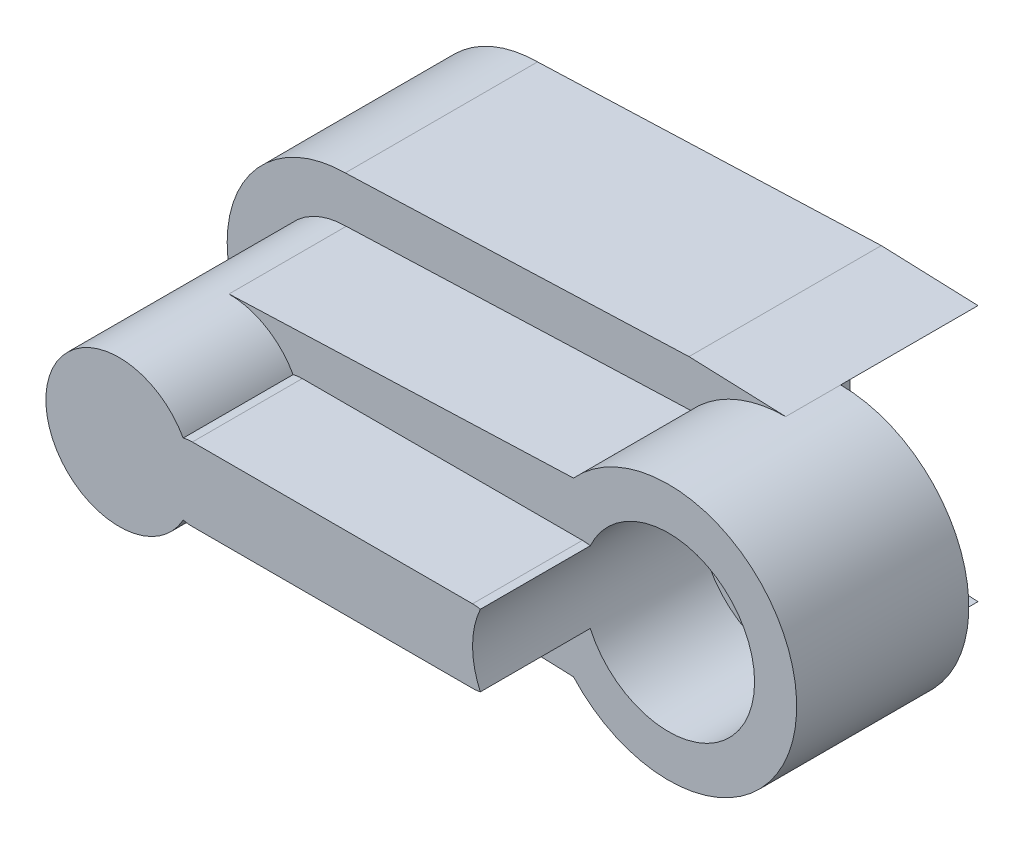
SolidWorks part; units mm, degrees
ref_plane "Front Plane" through (0, 0, 0) normal (0, 0, 1) x (1, 0, 0)
ref_plane "Top Plane" through (0, 0, 0) normal (0, 1, 0) x (1, 0, 0)
ref_plane "Right Plane" through (0, 0, 0) normal (1, 0, 0) x (0, 0, -1)
sketch "Sketch1" plane through (0, 0, 0) normal (0, 0, 1) x (1, 0, 0)
  line L4 (-10.9395, 2) -> (-1.5333, 2.35)
  line L5 (-10.9395, -2) -> (-1.5333, -2.35)
  circle A1 centre (1.0605, 0) radius 3.5
  circle A2 centre (-10.9395, 0) radius 2
  circle A3 centre (1.0605, 0) radius 2.35
  dimension "D2" = 7
  dimension "D6" = 4
  dimension "D1" = 4.7
  dimension "D5" = 4.7
  dimension "D7" = 12
  dimension "D8" = 9.4063
extrude "Boss-Extrude1" add sketch "Sketch1" along normal blind 6.7 contours A2 L5 A1 L4 | A1 | A2
sketch "Sketch2" plane through (0, 0, 6.7) normal (0, 0, 1) x (1, 0, 0)
  line L0 (-8.9395, 0) -> (-1.2895, 0) construction
  line L1 (-8.9395, 0) -> (-1.2895, 0) construction
  line L2 (-8.9395, 1) -> (-1.2895, 1)
  line L3 (-8.9395, -1) -> (-1.2895, -1)
  arc A1 (-9.1895, 0.9682) -> (-9.1895, -0.9682) centre (-10.9395, 0) ccw
  circle A2 centre (1.0605, 0) radius 2.35 construction
  arc A3 (-8.9395, 1) -> (-9.1895, 0.9682) centre (-8.9395, 0) ccw
  arc A4 (-1.2895, -1) -> (-1.0768, -0.9771) centre (-1.2895, 0) ccw
  arc A5 (-1.0768, 0.9771) -> (-1.0768, -0.9771) centre (1.0605, 0) ccw
  arc A6 (-1.0768, 0.9771) -> (-1.2895, 1) centre (-1.2895, 0) ccw
  arc A7 (-9.1895, -0.9682) -> (-8.9395, -1) centre (-8.9395, 0) ccw
  point P8 (-5.1145, 0)
extrude "Boss-Extrude2" add sketch "Sketch2" along normal blind 3
sketch "Sketch3" plane through (0, 0, 0) normal (0, 0, -1) x (-1, 0, 0)
  line L2 (10.9395, 2) -> (1.5333, 2.35)
  line L3 (1.5333, -2.35) -> (10.9395, -2)
  line L4 (10.9395, 2) -> (1.5333, 2.35)
  line L5 (1.5333, -2.35) -> (10.9395, -2)
  arc A2 (1.5333, 2.35) -> (1.5333, -2.35) centre (-1.0605, 0) ccw
  arc A3 (10.9395, -2) -> (10.9395, 2) centre (10.9395, 0) ccw
  arc A4 (1.5333, 2.35) -> (1.5333, -2.35) centre (-1.0605, 0) ccw
  arc A5 (10.9395, -2) -> (10.9395, 2) centre (10.9395, 0) ccw
  dimension "D1" = 0
extrude "Cut-Extrude1" cut sketch "Sketch3" against normal blind 2
sketch "Sketch4" plane through (0, 0, 2) normal (0, 0, -1) x (-1, 0, 0)
  circle A0 centre (-1.0605, 0) radius 1.45
  circle A1 centre (-1.0605, 0) radius 2.35
  dimension "D1" = 2.9
extrude "Boss-Extrude3" add sketch "Sketch4" against normal blind 1.5
sketch "Sketch5" plane through (0, 0, 2) normal (0, 0, -1) x (-1, 0, 0)
  line L0 (1.5797, -3.5991) -> (10.986, -3.2491)
  line L1 (10.986, 3.2491) -> (1.5797, 3.5991)
  line L3 (10.9656, 3.2499) -> (2.0599, 3.5813)
  line L7 (2.0599, -3.5813) -> (10.9656, -3.2499)
  line L8 (10.9395, 2) -> (1.5333, 2.35)
  line L9 (1.5333, -2.35) -> (10.9395, -2)
  line L10 (10.9395, 2) -> (1.5333, 2.35)
  line L11 (1.5333, -2.35) -> (10.9395, -2)
  line L13 (1.5797, -3.5991) -> (-1.0605, -3.5)
  line L14 (8.9395, -1) -> (1.2895, -1)
  line L15 (1.5333, -2.35) -> (10.9395, -2)
  line L16 (10.9395, 2) -> (1.5333, 2.35)
  line L17 (1.2895, 1) -> (8.9395, 1)
  line L19 (1.5333, -2.35) -> (10.9395, -2)
  line L20 (10.9395, 2) -> (1.5333, 2.35)
  line L22 (1.5797, 3.5991) -> (-1.0605, 3.5)
  arc A0 (10.9656, -3.2499) -> (10.9656, 3.2499) centre (10.9395, 0) ccw
  arc A6 (10.9395, -2) -> (10.9395, 2) centre (10.9395, 0) ccw
  arc A7 (1.5333, 2.35) -> (1.5333, -2.35) centre (-1.0605, 0) ccw
  arc A8 (10.9395, -2) -> (10.9395, 2) centre (10.9395, 0) ccw
  arc A10 (1.5333, 2.35) -> (1.5333, -2.35) centre (-1.0605, 0) ccw construction
  arc A11 (1.5333, 2.35) -> (-1.0605, 3.5) centre (-1.0605, 0) ccw
  arc A12 (1.2895, 1) -> (1.0768, 0.9771) centre (1.2895, 0) ccw
  arc A13 (1.0768, 0.9771) -> (1.0768, -0.9771) centre (-1.0605, 0) ccw
  arc A14 (1.0768, -0.9771) -> (1.2895, -1) centre (1.2895, 0) ccw
  arc A15 (8.9395, -1) -> (9.1895, -0.9682) centre (8.9395, 0) ccw
  arc A16 (9.1895, -0.9682) -> (10.9395, -2) centre (10.9395, 0) ccw
  arc A17 (1.5333, 2.35) -> (1.5333, -2.35) centre (-1.0605, 0) ccw
  arc A18 (10.9395, 2) -> (9.1895, 0.9682) centre (10.9395, 0) ccw
  arc A19 (9.1895, 0.9682) -> (8.9395, 1) centre (8.9395, 0) ccw
  arc A28 (2.0599, 3.5813) -> (2.0599, -3.5813) centre (-1.0605, 0) ccw construction
  arc A29 (1.5333, 2.35) -> (1.5333, -2.35) centre (-1.0605, 0) ccw construction
  arc A30 (-1.0605, -3.5) -> (1.5333, -2.35) centre (-1.0605, 0) ccw
  point P15 (18.4992, 0)
  dimension "D1" = 1.25
  dimension "D2" = 0
  dimension "D3" = 0
  dimension "D4" = 1.25
extrude "Boss-Extrude4" add sketch "Sketch5" against normal blind 1.5
sketch "Sketch7" plane through (0, 0, 2) normal (0, 0, -1) x (-1, 0, 0)
  line L4 (13.244, -2.2917) -> (0.8677, -2.921)
  line L5 (-1.0605, 0) -> (18.153, 0) construction
  line L6 (13.244, 2.2917) -> (0.8677, 2.921)
  line L8 (-1.0605, -3.5) -> (1.5797, -3.5991)
  line L9 (1.5797, -3.5991) -> (10.9656, -3.2499)
  line L10 (10.9656, 3.2499) -> (1.5797, 3.5991)
  line L11 (1.5797, 3.5991) -> (-1.0605, 3.5)
  line L12 (-1.0605, -3.5) -> (1.5797, -3.5991)
  line L13 (1.5797, -3.5991) -> (10.9656, -3.2499)
  line L14 (10.9656, 3.2499) -> (1.5797, 3.5991)
  line L15 (1.5797, 3.5991) -> (-1.0605, 3.5)
  arc A1 (0.8677, 2.921) -> (-1.0605, 3.5) centre (-1.0605, 0) ccw
  arc A2 (13.244, 2.2917) -> (10.9656, 3.2499) centre (10.9395, 0) ccw
  arc A3 (-1.0605, 3.5) -> (-1.0605, -3.5) centre (-1.0605, 0) ccw
  arc A4 (10.9656, -3.2499) -> (10.9656, 3.2499) centre (10.9395, 0) ccw
  arc A6 (10.9656, -3.2499) -> (13.244, -2.2917) centre (10.9395, 0) ccw
  arc A7 (-1.0605, -3.5) -> (0.8677, -2.921) centre (-1.0605, 0) ccw
  line M12 (-1.0605, -3.5) -> (1.5797, -3.5991)
  line M13 (1.5797, -3.5991) -> (10.9656, -3.2499)
  arc M14 (10.9656, -3.2499) -> (10.9656, 3.2499) centre (10.9395, 0) ccw
  line M15 (10.9656, 3.2499) -> (1.5797, 3.5991)
  line M16 (1.5797, 3.5991) -> (-1.0605, 3.5)
  dimension "D1" = 0
extrude "Boss-Extrude5" add sketch "Sketch7" along normal blind 1.75 contours A7 L4 M12 M13 M14 | A1 L6 M14 M15 M16
sketch "Sketch8" plane through (0, 0, 0.25) normal (0, 0, -1) x (-1, 0, 0)
  line L1 (10.9656, 3.2499) -> (1.5797, 3.5991) construction
  line L2 (1.5797, 3.5991) -> (-1.0605, 3.5) construction
  line L3 (-1.0605, -3.5) -> (1.5797, -3.5991) construction
  line L4 (1.5797, -3.5991) -> (10.9656, -3.2499) construction
  line L7 (10.9656, 3.2499) -> (1.5797, 3.5991)
  line L8 (1.5797, 3.5991) -> (-1.0605, 3.5)
  line L9 (-1.0605, -3.5) -> (1.5797, -3.5991)
  line L10 (1.5797, -3.5991) -> (10.9656, -3.2499)
  line L12 (13.244, -2.2917) -> (13.244, 2.2917)
  arc A1 (13.244, 2.2917) -> (10.9656, 3.2499) centre (10.9395, 0) ccw construction
  arc A3 (10.9656, -3.2499) -> (13.244, -2.2917) centre (10.9395, 0) ccw construction
  arc A5 (13.244, 2.2917) -> (10.9656, 3.2499) centre (10.9395, 0) ccw
  arc A7 (10.9656, -3.2499) -> (13.244, -2.2917) centre (10.9395, 0) ccw
  arc A10 (-1.0605, -3.5) -> (-1.0605, 3.5) centre (-1.0605, 0) ccw
extrude "Boss-Extrude6" add sketch "Sketch8" along normal blind 2
